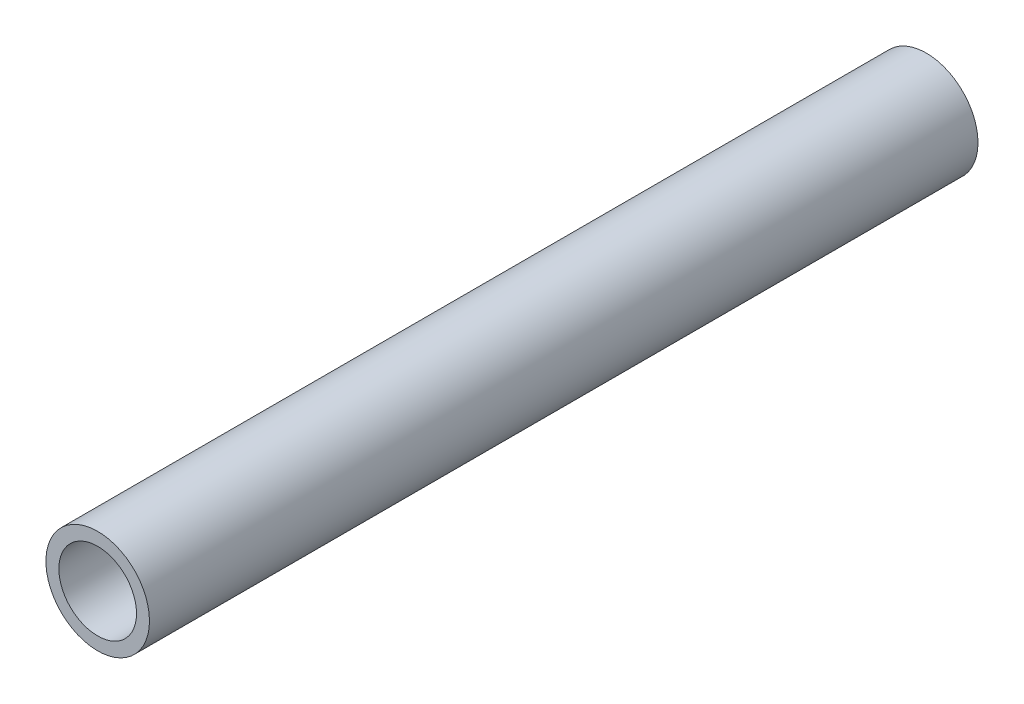
SolidWorks part; units mm, degrees
ref_plane "Front Plane" through (0, 0, 0) normal (0, 0, 1) x (1, 0, 0)
ref_plane "Top Plane" through (0, 0, 0) normal (0, 1, 0) x (1, 0, 0)
ref_plane "Right Plane" through (0, 0, 0) normal (1, 0, 0) x (0, 0, -1)
sketch "Sketch1" plane through (0, 0, 0) normal (0, 0, 1) x (1, 0, 0)
  circle A0 centre (0, 0) radius 10
  circle A1 centre (0, 0) radius 7.5
  dimension "D1" = 20
  dimension "D2" = 15
extrude "Boss-Extrude1" add sketch "Sketch1" along normal mid plane 160
